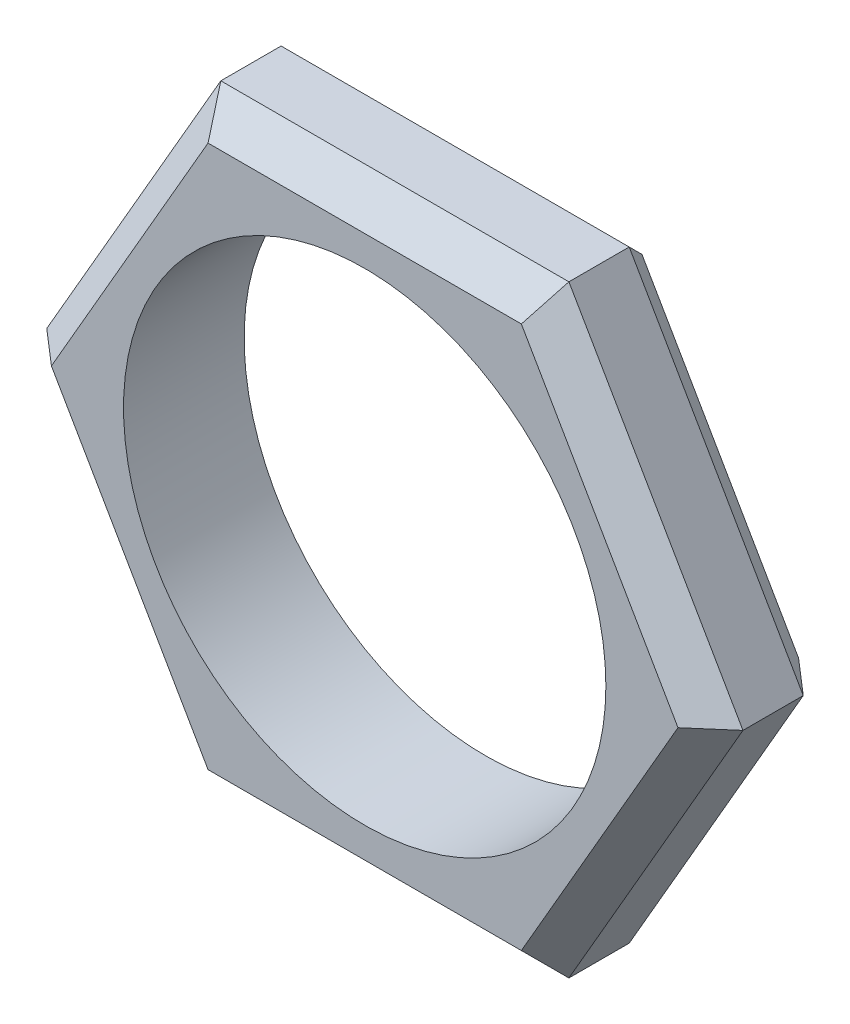
SolidWorks part; units mm, degrees
ref_plane "Front Plane" through (0, 0, 0) normal (0, 0, 1) x (1, 0, 0)
ref_plane "Top Plane" through (0, 0, 0) normal (0, 1, 0) x (1, 0, 0)
ref_plane "Right Plane" through (0, 0, 0) normal (1, 0, 0) x (0, 0, -1)
sketch "Sketch1" plane through (0, 0, 0) normal (0, 0, 1) x (1, 0, 0)
  line L1 (2.8868, 5) -> (-2.8868, 5)
  line L2 (-2.8868, 5) -> (-5.7735, 0)
  line L3 (-5.7735, 0) -> (-2.8868, -5)
  line L4 (-2.8868, -5) -> (2.8868, -5)
  line L5 (2.8868, -5) -> (5.7735, 0)
  line L6 (5.7735, 0) -> (2.8868, 5)
  circle A0 centre (0, 0) radius 5 construction
  circle A1 centre (0, 0) radius 4
  dimension "D2" = 8
  dimension "D1" = 10
extrude "Boss-Extrude1" add sketch "Sketch1" along normal blind 2
chamfer "Chamfer1" distance 0.5 angle 45 12 edges at (0, 5, 0) (-4.3301, 2.5, 0) (-4.3301, -2.5, 0) (0, -5, 0) (4.3301, -2.5, 0) (4.3301, 2.5, 0) (4.3301, -2.5, 2) (0, -5, 2) (-4.3301, -2.5, 2) (-4.3301, 2.5, 2) (0, 5, 2) (4.3301, 2.5, 2)
